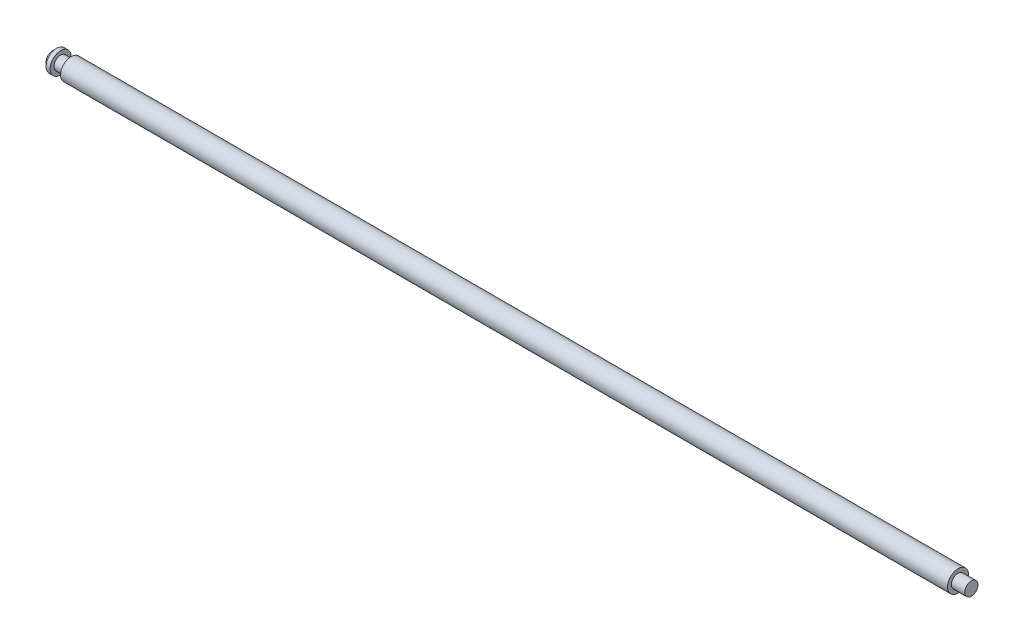
SolidWorks part; units mm, degrees
ref_plane "Alzado" through (0, 0, 0) normal (0, 0, 1) x (1, 0, 0)
ref_plane "Planta" through (0, 0, 0) normal (0, 1, 0) x (1, 0, 0)
ref_plane "Vista lateral" through (0, 0, 0) normal (1, 0, 0) x (0, 0, -1)
sketch "Croquis1" plane through (0, 0, 0) normal (0, 1, 0) x (1, 0, 0)
  line L0 (-195.85, 4.7625) -> (-195.85, 3)
  line L1 (-204.15, 0) -> (204.15, 0) construction
  line L2 (-195.85, 3) -> (-200.55, 3)
  line L3 (-195.85, 4.7625) -> (204.15, 4.7625)
  line L4 (204.15, 0) -> (204.15, 4.7625) construction
  line L5 (204.15, 4.7625) -> (204.15, 3)
  line L6 (204.15, 3) -> (210.15, 3)
  line L7 (210.15, 3) -> (210.15, 0)
  line L8 (-200.55, 3) -> (-200.55, 4.7625)
  line L9 (-200.55, 4.7625) -> (-202.4, 4.7625)
  line L10 (-202.4, 4.7625) -> (-202.4, 3)
  line L11 (-202.4, 3) -> (-204.15, 3)
  line L12 (-204.15, 3) -> (-204.15, 0)
  line L13 (-204.15, 0) -> (210.15, 0)
  point P4 (0, 0)
  dimension "D1" = 400
  dimension "D2" = 9.525
  dimension "D3" = 6
  dimension "D4" = 6
  dimension "D5" = 6
  dimension "D6" = 1.75
  dimension "D7" = 1.85
  dimension "D8" = 4.7
  dimension "D9" = 9.525
  dimension "D10" = 6
revolve "Revolución1" add sketch "Croquis1" angle 360 about L13
